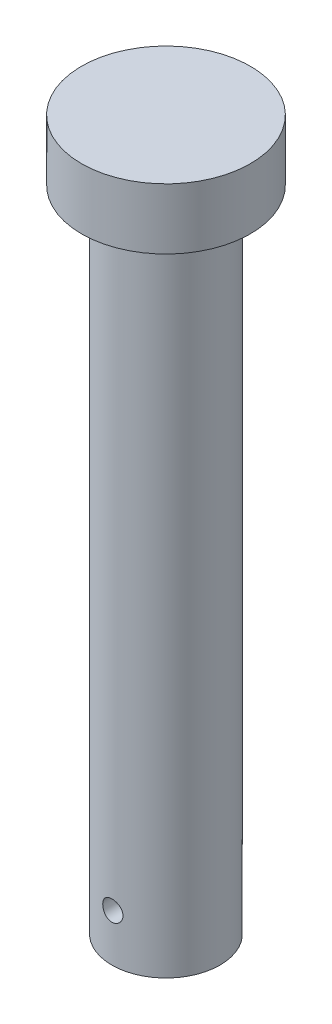
SolidWorks part; units mm, degrees
ref_plane "Front Plane" through (0, 0, 0) normal (0, 0, 1) x (1, 0, 0)
ref_plane "Top Plane" through (0, 0, 0) normal (0, 1, 0) x (1, 0, 0)
ref_plane "Right Plane" through (0, 0, 0) normal (1, 0, 0) x (0, 0, -1)
sketch "Sketch1" plane through (0, 0, 0) normal (0, 1, 0) x (1, 0, 0)
  circle A0 centre (0, 0) radius 12.5
  dimension "D1" = 25
extrude "Boss-Extrude1" add sketch "Sketch1" along normal blind 9
sketch "Sketch2" plane through (0, 0, 0) normal (0, -1, 0) x (1, 0, 0)
  circle A0 centre (0, 0) radius 8
  dimension "D1" = 16
extrude "Boss-Extrude2" add sketch "Sketch2" along normal blind 96
sketch "Sketch3" plane through (0, 0, 0) normal (0, 0, 1) x (1, 0, 0)
  line L0 (0, -95.9851) -> (0, -62.4778) construction
  line L1 (-8, -96) -> (8, -96) construction
  circle A0 centre (0, -89) radius 1.5
  dimension "D1" = 3
  dimension "D2" = 7
extrude "Cut-Extrude1" cut sketch "Sketch3" against normal mid plane 96
